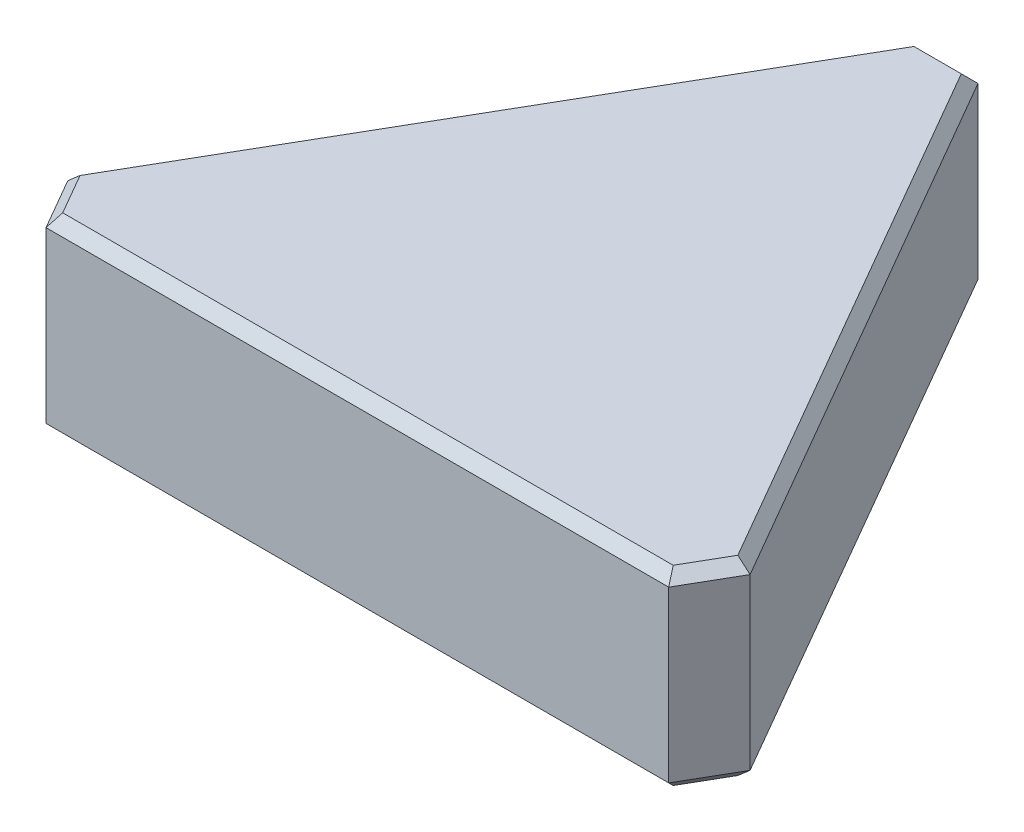
SolidWorks part; units mm, degrees
ref_plane "Plan de face" through (0, 0, 0) normal (0, 0, 1) x (1, 0, 0)
ref_plane "Plan de dessus" through (0, 0, 0) normal (0, 1, 0) x (1, 0, 0)
ref_plane "Plan de droite" through (0, 0, 0) normal (1, 0, 0) x (0, 0, -1)
sketch "Esquisse1" plane through (0, 0, 0) normal (0, 1, 0) x (1, 0, 0)
  line L0 (-70, 0) -> (70, 0)
  line L2 (70, 0) -> (0, 121.2436)
  line L3 (0, 121.2436) -> (-70, 0)
  point P0 (0, 121.2436)
  point P7 (0, 0)
  dimension "D2" = 70
extrude "Boss.-Extru.1" add sketch "Esquisse1" along normal blind 36
chamfer "Chanfrein1" distance 11.24 angle 60 3 edges at (-70, 18, 0) (0, 18, -121.2436) (70, 18, 0)
chamfer "Chanfrein2" distance 2 angle 45 6 edges at (0, 36, 0) (61.57, 36, -4.8671) (35, 36, -60.6218) (0, 36, -111.5094) (-35, 36, -60.6218) (-61.57, 36, -4.8671)
chamfer "Chanfrein3" distance 2 angle 45 6 edges at (61.57, 0, -4.8671) (0, 0, 0) (-61.57, 0, -4.8671) (-35, 0, -60.6218) (35, 0, -60.6218) (0, 0, -111.5094)
